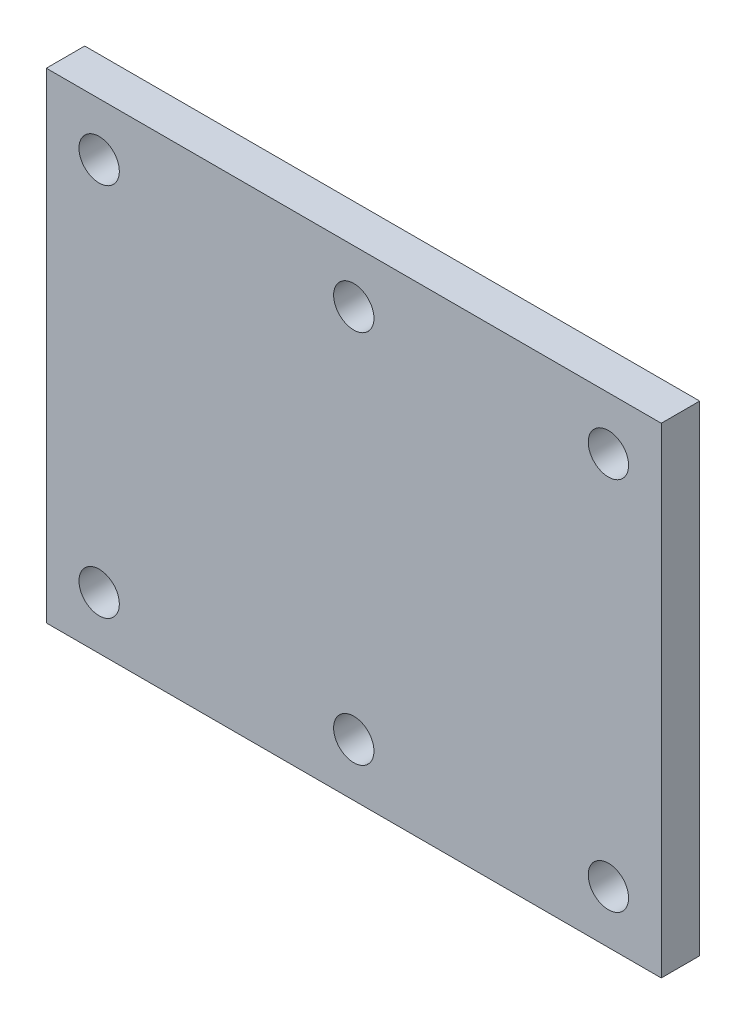
SolidWorks part; units mm, degrees
ref_plane "Front Plane" through (0, 0, 0) normal (0, 0, 1) x (1, 0, 0)
ref_plane "Top Plane" through (0, 0, 0) normal (0, 1, 0) x (1, 0, 0)
ref_plane "Right Plane" through (0, 0, 0) normal (1, 0, 0) x (0, 0, -1)
sketch "Sketch1" plane through (0, 0, 0) normal (0, 0, 1) x (1, 0, 0)
  line L1 (-26.5, 19.5) -> (26.5, 19.5) construction
  line L2 (-26.5, 19.5) -> (-26.5, -19.5) construction
  line L3 (-26.5, -19.5) -> (26.5, -19.5) construction
  line L4 (26.5, 19.5) -> (26.5, -19.5) construction
  line L5 (0, -19.5) -> (0, 19.5) construction
  line L6 (-26.5, 0) -> (26.5, 0) construction
  line L7 (-32, 25) -> (32, 25)
  line L8 (-32, 25) -> (-32, -25)
  line L9 (-32, -25) -> (32, -25)
  line L10 (32, 25) -> (32, -25)
  line L11 (0, -25) -> (0, 25) construction
  line L12 (-32, 0) -> (32, 0) construction
  circle A0 centre (-26.5, 19.5) radius 2.1
  circle A1 centre (26.5, 19.5) radius 2.1
  circle A2 centre (-26.5, -19.5) radius 2.1
  circle A3 centre (26.5, -19.5) radius 2.1
  circle A4 centre (0, 19.5) radius 2.1
  circle A5 centre (0, -19.5) radius 2.1
  point P0 (0, 0)
  point P10 (0, 0)
  dimension "D3" = 4.2
  dimension "D1" = 39
  dimension "D2" = 53
  dimension "D4" = 50
  dimension "D5" = 64
extrude "Boss-Extrude1" add sketch "Sketch1" along normal blind 4
